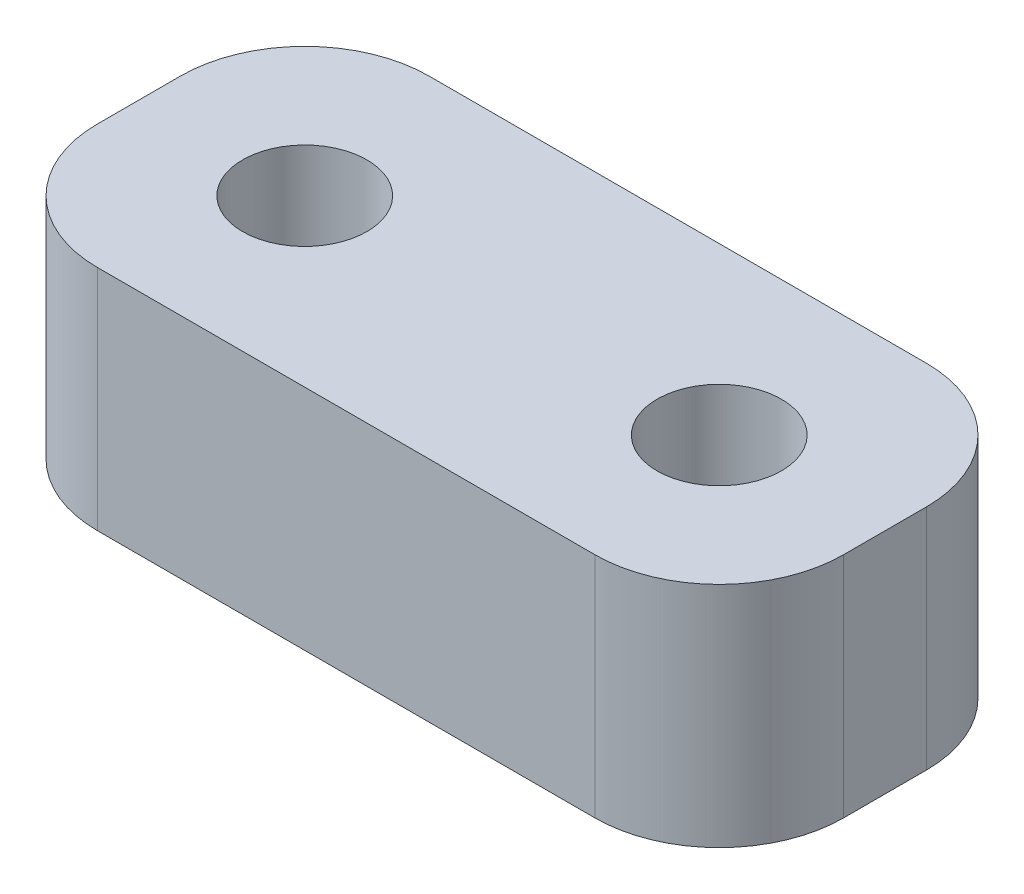
SolidWorks part; units mm, degrees
ref_plane "Front Plane" through (0, 0, 0) normal (0, 0, 1) x (1, 0, 0)
ref_plane "Top Plane" through (0, 0, 0) normal (0, 1, 0) x (1, 0, 0)
ref_plane "Right Plane" through (0, 0, 0) normal (1, 0, 0) x (0, 0, -1)
sketch "Sketch1" plane through (0, 0, 0) normal (0, 1, 0) x (1, 0, 0)
  line L1 (0, 0) -> (18, 0)
  line L2 (0, 0) -> (0, 8)
  line L3 (0, 8) -> (18, 8)
  line L4 (18, 0) -> (18, 8)
  circle A0 centre (4, 4) radius 1.5
  circle A1 centre (14, 4) radius 1.5
  dimension "D3" = 3
  dimension "D4" = 3
  dimension "D1" = 18
  dimension "D2" = 10
  dimension "D5" = 4
  dimension "D6" = 4
  dimension "D7" = 4
  dimension "D8" = 8
extrude "Boss-Extrude1" add sketch "Sketch1" along normal blind 5.5
fillet "Fillet1" radius 3 4 edges at (0, 2.75, -8) (0, 2.75, 0) (18, 2.75, -8) (18, 2.75, 0)
